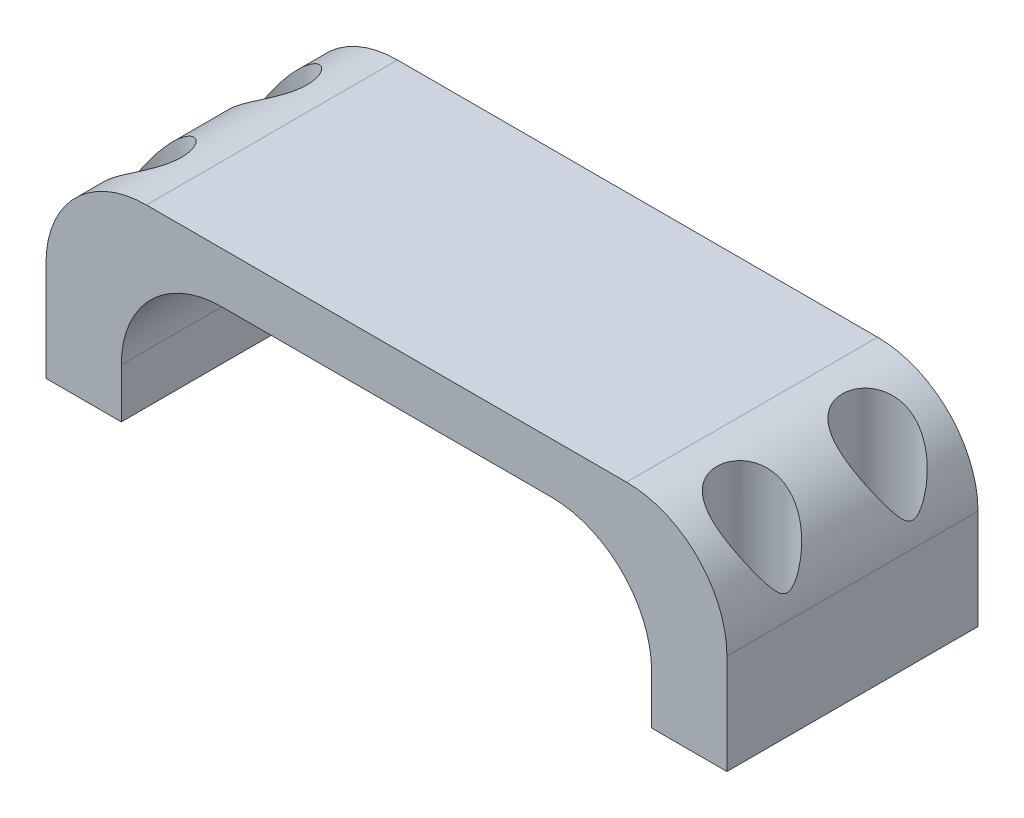
SolidWorks part; units mm, degrees
material "6061-T6 (SS)"
ref_plane "Front Plane" through (0, 0, 0) normal (0, 0, 1) x (1, 0, 0)
ref_plane "Top Plane" through (0, 0, 0) normal (0, 1, 0) x (1, 0, 0)
ref_plane "Right Plane" through (0, 0, 0) normal (1, 0, 0) x (0, 0, -1)
sketch "Sketch1" plane through (0, 0, 0) normal (0, 0, 1) x (1, 0, 0)
  line L0 (-58.2733, -9.2979) -> (-58.2733, -3.0414)
  line L1 (-67.7983, -9.2979) -> (-67.7983, 3.347)
  line L2 (-67.7983, -9.2979) -> (-58.2733, -9.2979)
  line L3 (8.7827, -9.2979) -> (8.7827, -3.0414)
  line L4 (18.3077, -9.2979) -> (18.3077, 3.347)
  line L5 (5.6077, 16.047) -> (-55.0983, 16.047)
  line L6 (-45.5733, 9.6586) -> (-3.9173, 9.6586)
  line L7 (8.7827, -9.2979) -> (18.3077, -9.2979)
  arc A0 (-3.9173, 9.6586) -> (8.7827, -3.0414) centre (-3.9173, -3.0414) cw
  arc A1 (-45.5733, 9.6586) -> (-58.2733, -3.0414) centre (-45.5733, -3.0414) ccw
  arc A2 (5.6077, 16.047) -> (18.3077, 3.347) centre (5.6077, 3.347) cw
  arc A3 (-55.0983, 16.047) -> (-67.7983, 3.347) centre (-55.0983, 3.347) ccw
  dimension "D1" = 12.7
  dimension "D2" = 12.7
  dimension "D3" = 67.056
  dimension "D4" = 9.525
  dimension "D5" = 9.525
extrude "Boss-Extrude1" add sketch "Sketch1" along normal blind 31.75
sketch "Sketch2" plane through (0, -9.2979, 0) normal (0, -1, 0) x (1, 0, 0)
  line L0 (-67.7983, 15.875) -> (-58.2733, 15.875) construction
  line L1 (-67.7983, 31.75) -> (-67.7983, 0) construction
  line L2 (-58.2733, 31.75) -> (-58.2733, 0) construction
  line L3 (8.7827, 15.875) -> (18.3077, 15.875) construction
  line L4 (8.7827, 31.75) -> (8.7827, 0) construction
  line L5 (18.3077, 31.75) -> (18.3077, 0) construction
  line L6 (18.3077, 15.875) -> (13.5452, 31.75) construction
  line L7 (8.7827, 31.75) -> (18.3077, 31.75) construction
  line L8 (13.5452, 31.75) -> (13.5452, 15.875) construction
  line L9 (13.5452, 15.875) -> (13.5452, 0) construction
  line L10 (8.7827, 0) -> (18.3077, 0) construction
  line L11 (-58.2733, 15.875) -> (-63.0358, 31.75) construction
  line L12 (-67.7983, 31.75) -> (-58.2733, 31.75) construction
  line L13 (-63.0358, 31.75) -> (-63.0358, 15.875) construction
  line L14 (-63.0358, 15.875) -> (-63.0358, 0) construction
  line L15 (-67.7983, 0) -> (-58.2733, 0) construction
  circle A0 centre (-63.0358, 7.9375) radius 3.175
  circle A1 centre (-63.0358, 23.8125) radius 3.175
  circle A2 centre (13.5452, 23.8125) radius 3.175
  circle A3 centre (13.5452, 7.9375) radius 3.175
  dimension "D1" = 6.35
  dimension "D2" = 6.35
  dimension "D3" = 6.35
  dimension "D4" = 6.35
extrude "Cut-Extrude1" cut sketch "Sketch2" against normal blind 37.084
ref_plane "Plane1" through (0, -2.9479, 0) normal (0, -1, 0) x (-1, 0, 0)
sketch "Sketch3" plane through (0, -2.9479, 0) normal (0, -1, 0) x (-1, 0, 0)
  circle A0 centre (-13.5452, -23.8125) radius 4.445
  circle A1 centre (-13.5452, -7.9375) radius 4.445
  circle A2 centre (63.0358, -23.8125) radius 4.445
  circle A3 centre (63.0358, -7.9375) radius 4.445
  dimension "D1" = 8.89
  dimension "D2" = 8.89
  dimension "D3" = 8.89
  dimension "D4" = 8.89
extrude "Cut-Extrude2" cut sketch "Sketch3" against normal blind 37.084
